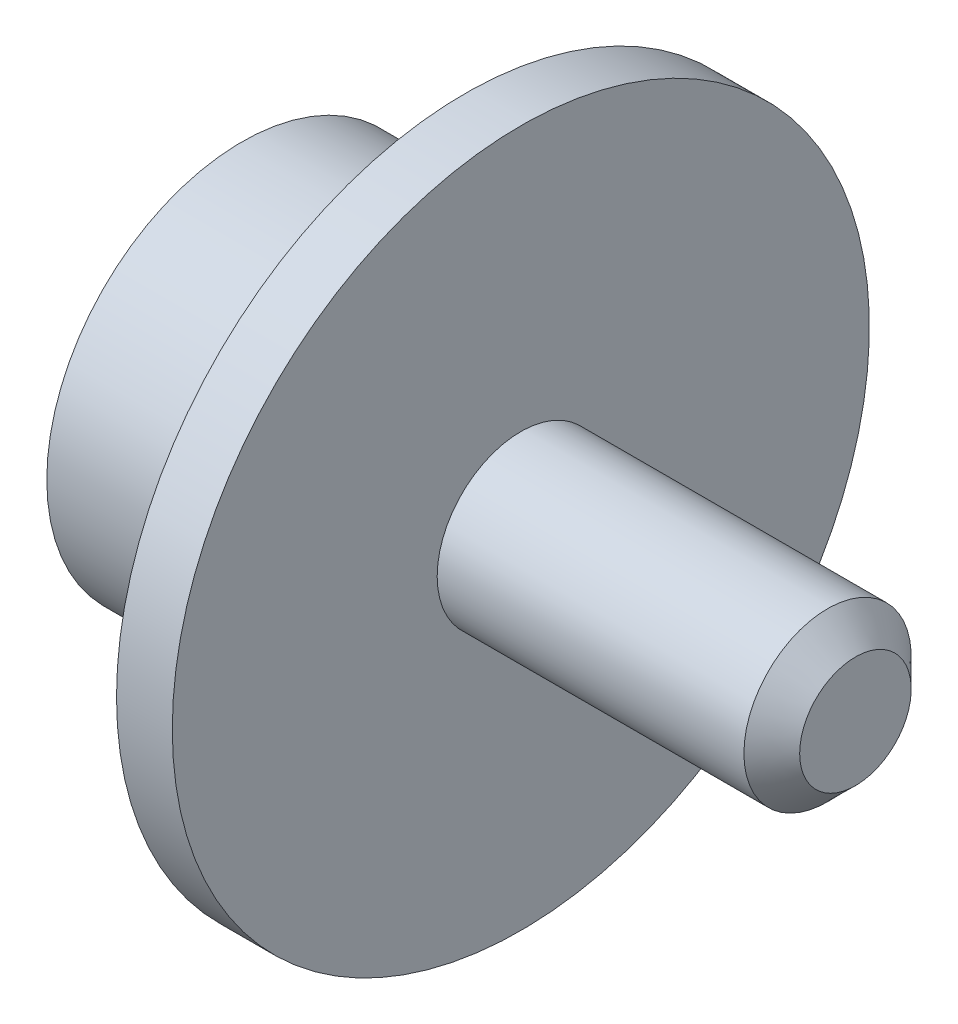
SolidWorks part; units mm, degrees
ref_plane "Front Plane" through (0, 0, 0) normal (0, 0, 1) x (1, 0, 0)
ref_plane "Top Plane" through (0, 0, 0) normal (0, 1, 0) x (1, 0, 0)
ref_plane "Right Plane" through (0, 0, 0) normal (1, 0, 0) x (0, 0, -1)
sketch "Sketch2" plane through (0, 0, 0) normal (0, 0, 1) x (1, 0, 0)
  line L0 (0, 0) -> (19.4428, 0) construction
  line L1 (7, 0) -> (7, 5.5)
  line L2 (7, 5.5) -> (0, 5.5)
  line L3 (0, 5.5) -> (0, 7)
  line L4 (0, 7) -> (8, 7)
  line L5 (8, 7) -> (8, 12.5)
  line L6 (8, 12.5) -> (10, 12.5)
  line L7 (10, 12.5) -> (10, 3)
  line L8 (10, 3) -> (22, 3)
  line L9 (22, 3) -> (22, 0)
  line L10 (22, 0) -> (7, 0)
  dimension "D1" = 7
  dimension "D2" = 22
  dimension "D3" = 12
  dimension "D4" = 12.5
  dimension "D5" = 8
  dimension "D6" = 7
  dimension "D7" = 5.5
  dimension "D8" = 3
revolve "Revolve1" add sketch "Sketch2" angle 360 about L0
chamfer "Chamfer1" distance 1 angle 45 1 edges at (22, 0, 3)
